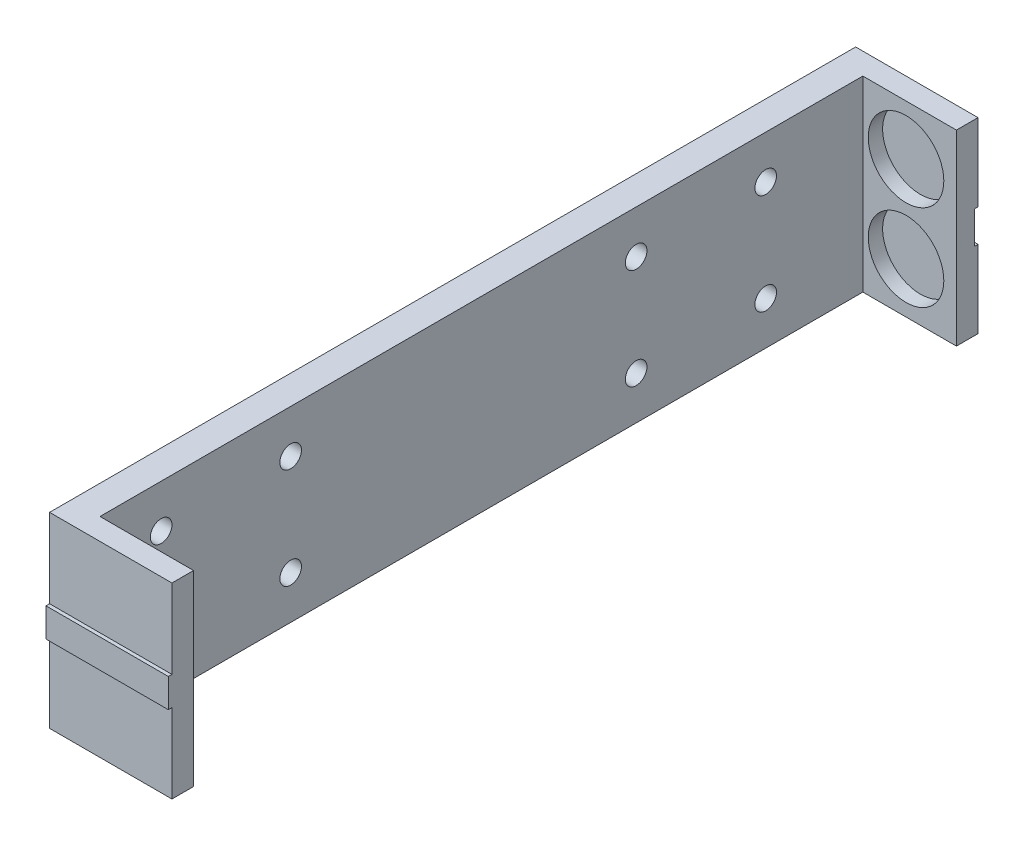
SolidWorks part; units mm, degrees
ref_plane "Plan de face" through (0, 0, 0) normal (0, 0, 1) x (1, 0, 0)
ref_plane "Plan de dessus" through (0, 0, 0) normal (0, 1, 0) x (1, 0, 0)
ref_plane "Plan de droite" through (0, 0, 0) normal (1, 0, 0) x (0, 0, -1)
sketch "Esquisse1" plane through (0, 0, 0) normal (0, 0, 1) x (1, 0, 0)
  line L1 (0, 0) -> (17, 0)
  line L2 (0, 0) -> (0, 26)
  line L3 (0, 26) -> (17, 26)
  line L4 (17, 0) -> (17, 26)
  dimension "D1" = 17
  dimension "D2" = 26
extrude "Boss.-Extru.1" add sketch "Esquisse1" along normal blind 3
sketch "Esquisse3" plane through (0, 0, 0) normal (0, 0, -1) x (-1, 0, 0)
  line L0 (0, 0) -> (-17, 0) construction
  line L1 (0, 26) -> (-4, 26)
  line L2 (0, 26) -> (0, 0)
  line L3 (0, 0) -> (-4, 0)
  line L4 (-4, 26) -> (-4, 0)
  dimension "D1" = 4
extrude "Boss.-Extru.2" add sketch "Esquisse3" along normal blind 109
sketch "Esquisse4" plane through (0, 0, 0) normal (-1, 0, 0) x (0, 0, 1)
  line L0 (3, 26) -> (-109, 26) construction
  line L1 (3, 0) -> (-109, 0) construction
  line L2 (3, 26) -> (3, 0) construction
  circle A0 centre (-8.5, 20) radius 1.5
  circle A1 centre (-8.5, 6) radius 1.5
  circle A2 centre (-26.4967, 20) radius 1.5
  circle A3 centre (-26.4967, 6) radius 1.5
  dimension "D1" = 3
  dimension "D2" = 3
  dimension "D7" = 3
  dimension "D8" = 3
  dimension "D3" = 6
  dimension "D4" = 6
  dimension "D5" = 11.5
  dimension "D6" = 11.5
  dimension "D9" = 17.9967
  dimension "D10" = 17.9967
  dimension "D11" = 6
  dimension "D12" = 6
extrude "Enlèv. mat.-Extru.2" cut sketch "Esquisse4" against normal blind 4
sketch "Esquisse5" plane through (0, 0, 0) normal (-1, 0, 0) x (0, 0, 1)
  line L0 (3, 26) -> (-109, 26) construction
  line L1 (3, 0) -> (-109, 0) construction
  line L2 (-109, 0) -> (-109, 26) construction
  circle A0 centre (-92.5, 19.9995) radius 1.5
  circle A1 centre (-92.5, 6) radius 1.5
  circle A2 centre (-74.5, 19.9995) radius 1.5
  circle A3 centre (-74.5, 6) radius 1.5
  dimension "D5" = 3
  dimension "D6" = 3
  dimension "D7" = 3
  dimension "D8" = 3
  dimension "D1" = 6.0005
  dimension "D2" = 6
  dimension "D3" = 16.5
  dimension "D4" = 16.5
  dimension "D9" = 18
  dimension "D10" = 18
  dimension "D11" = 6
  dimension "D12" = 6.0005
extrude "Enlèv. mat.-Extru.3" cut sketch "Esquisse5" against normal blind 4
sketch "Esquisse6" plane through (4, 0, 0) normal (1, 0, 0) x (0, 0, -1)
  line L0 (109, 26) -> (0, 26) construction
  line L1 (109, 0) -> (106, 0)
  line L2 (109, 0) -> (109, 26)
  line L3 (109, 26) -> (106, 26)
  line L4 (106, 0) -> (106, 26)
  dimension "D1" = 3
extrude "Boss.-Extru.3" add sketch "Esquisse6" along normal blind 13
sketch "Esquisse8" plane through (0, 0, 0) normal (0, 0, -1) x (-1, 0, 0)
  line L0 (-4, 0) -> (-17, 0) construction
  line L1 (-17, 0) -> (-17, 26) construction
  line L2 (-17, 26) -> (-4, 26) construction
  circle A0 centre (-10, 7) radius 5.25
  circle A1 centre (-10, 19) radius 5.25
  dimension "D1" = 10.5
  dimension "D2" = 10.5
  dimension "D3" = 7
  dimension "D4" = 7
  dimension "D5" = 7
  dimension "D6" = 7
extrude "Enlèv. mat.-Extru.4" cut sketch "Esquisse8" against normal blind 2
sketch "Esquisse9" plane through (0, 0, -106) normal (0, 0, 1) x (1, 0, 0)
  line L0 (17, 26) -> (17, 0) construction
  line L1 (17, 26) -> (4, 26) construction
  line L2 (17, 0) -> (4, 0) construction
  circle A0 centre (10, 19) radius 5.25
  circle A1 centre (10, 7) radius 5.25
  dimension "D1" = 10.5
  dimension "D2" = 10.5
  dimension "D3" = 7
  dimension "D4" = 7
  dimension "D5" = 7
  dimension "D6" = 7
extrude "Enlèv. mat.-Extru.5" cut sketch "Esquisse9" against normal blind 2
sketch "Esquisse10" plane through (0, 0, 3) normal (0, 0, 1) x (1, 0, 0)
  line L0 (0, 26) -> (0, 0) construction
  line L1 (0, 11) -> (17, 11)
  line L2 (0, 11) -> (0, 15)
  line L3 (0, 15) -> (17, 15)
  line L4 (17, 11) -> (17, 15)
  line L5 (17, 0) -> (17, 26) construction
  line L6 (17, 26) -> (0, 26) construction
  line L7 (0, 0) -> (17, 0) construction
  dimension "D1" = 11
  dimension "D2" = 11
  dimension "D3" = 4
extrude "Boss.-Extru.5" add sketch "Esquisse10" along normal blind 0.5
sketch "Esquisse11" plane through (0, 0, -109) normal (0, 0, -1) x (-1, 0, 0)
  line L0 (-17, 0) -> (-17, 26) construction
  line L1 (-17, 15.25) -> (0, 15.25)
  line L2 (-17, 15.25) -> (-17, 10.75)
  line L3 (-17, 10.75) -> (0, 10.75)
  line L4 (0, 15.25) -> (0, 10.75)
  line L5 (0, 0) -> (0, 26) construction
  line L6 (0, 26) -> (-17, 26) construction
  line L7 (-17, 0) -> (0, 0) construction
  dimension "D1" = 10.75
  dimension "D2" = 10.75
  dimension "D3" = 4.5
extrude "Enlèv. mat.-Extru.6" cut sketch "Esquisse11" against normal blind 0.5
